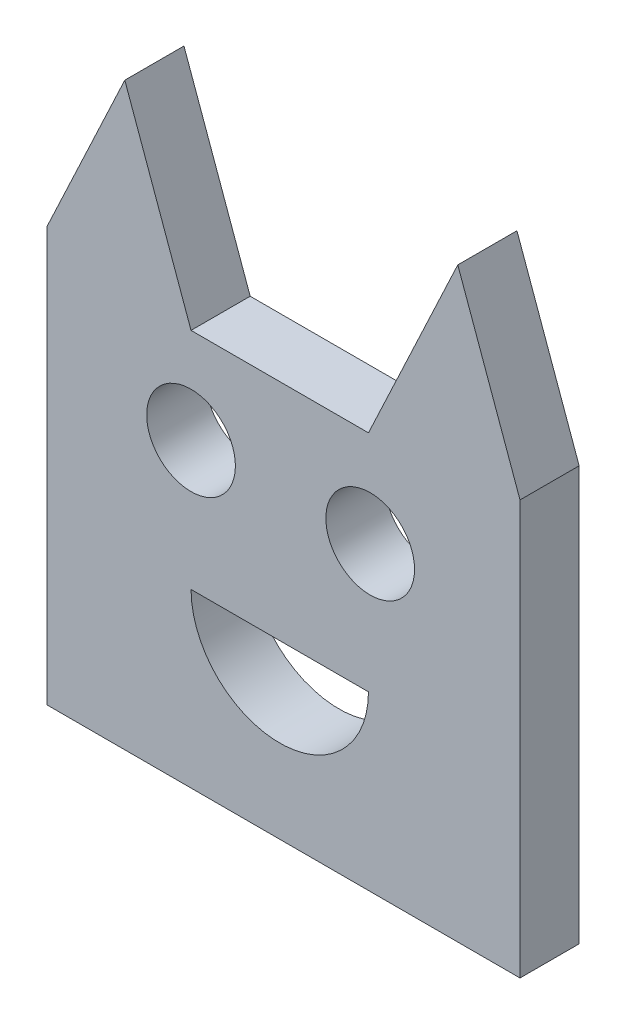
SolidWorks part; units mm, degrees
ref_plane "前基準面" through (0, 0, 0) normal (0, 0, 1) x (1, 0, 0)
ref_plane "上基準面" through (0, 0, 0) normal (0, 1, 0) x (1, 0, 0)
ref_plane "右基準面" through (0, 0, 0) normal (1, 0, 0) x (0, 0, -1)
sketch "草圖1" plane through (0, 0, 0) normal (0, 0, 1) x (1, 0, 0)
  line L0 (0, 0) -> (30, 0)
  line L1 (30, 0) -> (45.1012, 32.1446)
  line L2 (45.1012, 32.1446) -> (55.6206, 2.984)
  line L3 (0, 0) -> (-11.198, 31.042)
  line L4 (-11.198, 31.042) -> (-24.3794, 2.984)
  line L5 (-24.3794, 2.984) -> (-24.3794, -67.016)
  line L6 (-24.3794, -67.016) -> (55.6206, -67.016)
  line L7 (55.6206, -67.016) -> (55.6206, 2.984)
  line L8 (0, -37.9284) -> (30, -37.9284)
  circle A0 centre (0, -16.11) radius 7.5
  circle A1 centre (30.2918, -16.11) radius 7.5
  circle A2 centre (0, -16.11) radius 2.5
  circle A3 centre (30.2918, -16.11) radius 2.5
  arc A4 (0, -37.9284) -> (30, -37.9284) centre (15, -37.9284) ccw
  dimension "D7" = 30
  dimension "D11" = 5
  dimension "D12" = 15
  dimension "D13" = 5
  dimension "D14" = 15
  dimension "D1" = 45
  dimension "D2" = 45
  dimension "D3" = 70
  dimension "D4" = 70
  dimension "D5" = 80
  dimension "D6" = 30
  dimension "D8" = 31
  dimension "D9" = 31
  dimension "D10" = 33
extrude "填料-伸長1" add sketch "草圖1" against normal blind 10 contours L6 L7 L2 L1 L0 L3 L4 L5 A4 L8 A1 A0
